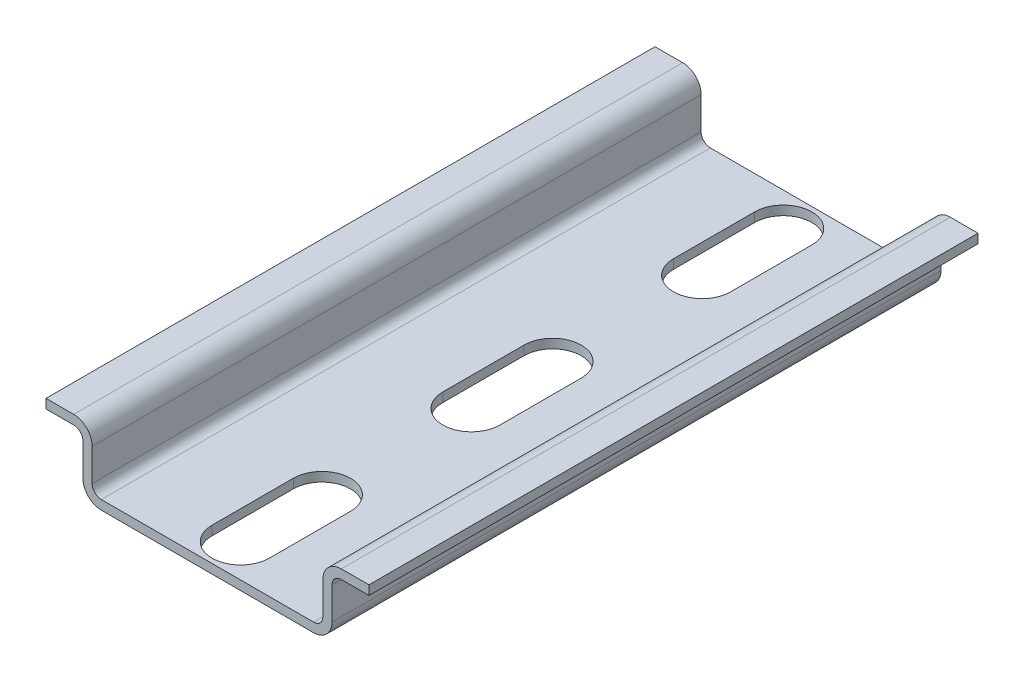
SolidWorks part; units mm, degrees
ref_plane "Спереди" through (0, 0, 0) normal (0, 0, 1) x (1, 0, 0)
ref_plane "Сверху" through (0, 0, 0) normal (0, 1, 0) x (1, 0, 0)
ref_plane "Справа" through (0, 0, 0) normal (1, 0, 0) x (0, 0, -1)
sketch "Эскиз1" plane through (0, 0, 0) normal (0, 0, 1) x (1, 0, 0)
  line L0 (0, 6.5) -> (0, -29.2061) construction
  line L1 (-17.5, 6.5) -> (-14.5, 6.5)
  line L2 (-13.5, 5.5) -> (-13.5, 2)
  line L3 (-11.5, 1) -> (11.5, 1)
  line L4 (-11.5, 0) -> (11.5, 0)
  line L5 (-12.5, 5.5) -> (-12.5, 2)
  line L6 (-17.5, 7.5) -> (-14.5, 7.5)
  line L7 (-17.5, 7.5) -> (-17.5, 6.5)
  line L8 (12.5, 5.5) -> (12.5, 2)
  line L9 (13.5, 5.5) -> (13.5, 2)
  line L10 (17.5, 6.5) -> (14.5, 6.5)
  line L11 (17.5, 7.5) -> (17.5, 6.5)
  line L12 (17.5, 7.5) -> (14.5, 7.5)
  arc A0 (-14.5, 6.5) -> (-13.5, 5.5) centre (-14.5, 5.5) cw
  arc A1 (13.5, 2) -> (11.5, 0) centre (11.5, 2) cw
  arc A2 (-14.5, 7.5) -> (-12.5, 5.5) centre (-14.5, 5.5) cw
  arc A3 (-13.5, 2) -> (-11.5, 0) centre (-11.5, 2) ccw
  arc A4 (14.5, 7.5) -> (12.5, 5.5) centre (14.5, 5.5) ccw
  arc A5 (14.5, 6.5) -> (13.5, 5.5) centre (14.5, 5.5) ccw
  arc A6 (-11.5, 1) -> (-12.5, 2) centre (-11.5, 2) cw
  arc A7 (12.5, 2) -> (11.5, 1) centre (11.5, 2) cw
  point P9 (-13.5, 6.5)
  point P11 (13.5, 0)
  point P12 (-13.5, 0)
  point P18 (0, 0)
  point P19 (0, 1)
  point P34 (-13.5, 0)
  dimension "D1" = 13.5
  dimension "D2" = 6.5
  dimension "D3" = 17.5
  dimension "D5" = 1
extrude "Вытянуть1" add sketch "Эскиз1" along normal blind 220
sketch "Эскиз2" plane through (0, 1, 0) normal (0, 1, 0) x (-1, 0, 0)
  line L0 (0, -5.0137) -> (0, 104.2733) construction
  line L1 (-11.5, 0) -> (11.5, 0) construction
  line L3 (3.1, 21.9) -> (3.1, 13.1)
  line L5 (-3.1, 21.9) -> (-3.1, 13.1)
  arc A0 (3.1, 13.1) -> (-3.1, 13.1) centre (0, 13.1) cw
  arc A1 (-3.1, 21.9) -> (3.1, 21.9) centre (0, 21.9) cw
  dimension "D2" = 10
  dimension "D3" = 15
  dimension "D1" = 6.2
extrude "Вырез-Вытянуть1" cut sketch "Эскиз2" against normal blind 1
pattern_linear "Линейный массив3" count 8 spacing 25 along (0, 0, 1) of "Вырез-Вытянуть1"
sketch "Эскиз3" plane through (0, 0, 0) normal (0, 0, -1) x (-1, 0, 0)
  line L12 (17.5, 6.5) -> (17.5, 7.5)
  line L13 (17.5, 7.5) -> (14.5, 7.5)
  line L14 (12.5, 5.5) -> (12.5, 2)
  line L15 (11.5, 1) -> (-11.5, 1)
  line L16 (-12.5, 2) -> (-12.5, 5.5)
  line L17 (-14.5, 7.5) -> (-17.5, 7.5)
  line L18 (-17.5, 7.5) -> (-17.5, 6.5)
  line L19 (-17.5, 6.5) -> (-14.5, 6.5)
  line L20 (-13.5, 5.5) -> (-13.5, 2)
  line L21 (-11.5, 0) -> (11.5, 0)
  line L22 (13.5, 2) -> (13.5, 5.5)
  line L23 (14.5, 6.5) -> (17.5, 6.5)
  line L24 (17.5, 6.5) -> (17.5, 7.5)
  line L25 (17.5, 7.5) -> (14.5, 7.5)
  line L26 (12.5, 5.5) -> (12.5, 2)
  line L27 (11.5, 1) -> (-11.5, 1)
  line L28 (-12.5, 2) -> (-12.5, 5.5)
  line L29 (-14.5, 7.5) -> (-17.5, 7.5)
  line L30 (-17.5, 7.5) -> (-17.5, 6.5)
  line L31 (-17.5, 6.5) -> (-14.5, 6.5)
  line L32 (-13.5, 5.5) -> (-13.5, 2)
  line L33 (-11.5, 0) -> (11.5, 0)
  line L34 (13.5, 2) -> (13.5, 5.5)
  line L35 (14.5, 6.5) -> (17.5, 6.5)
  arc A8 (14.5, 7.5) -> (12.5, 5.5) centre (14.5, 5.5) ccw
  arc A9 (11.5, 1) -> (12.5, 2) centre (11.5, 2) ccw
  arc A10 (-12.5, 2) -> (-11.5, 1) centre (-11.5, 2) ccw
  arc A11 (-12.5, 5.5) -> (-14.5, 7.5) centre (-14.5, 5.5) ccw
  arc A12 (-13.5, 5.5) -> (-14.5, 6.5) centre (-14.5, 5.5) ccw
  arc A13 (-13.5, 2) -> (-11.5, 0) centre (-11.5, 2) ccw
  arc A14 (11.5, 0) -> (13.5, 2) centre (11.5, 2) ccw
  arc A15 (14.5, 6.5) -> (13.5, 5.5) centre (14.5, 5.5) ccw
  arc A16 (14.5, 7.5) -> (12.5, 5.5) centre (14.5, 5.5) ccw
  arc A17 (11.5, 1) -> (12.5, 2) centre (11.5, 2) ccw
  arc A18 (-12.5, 2) -> (-11.5, 1) centre (-11.5, 2) ccw
  arc A19 (-12.5, 5.5) -> (-14.5, 7.5) centre (-14.5, 5.5) ccw
  arc A20 (-13.5, 5.5) -> (-14.5, 6.5) centre (-14.5, 5.5) ccw
  arc A21 (-13.5, 2) -> (-11.5, 0) centre (-11.5, 2) ccw
  arc A22 (11.5, 0) -> (13.5, 2) centre (11.5, 2) ccw
  arc A23 (14.5, 6.5) -> (13.5, 5.5) centre (14.5, 5.5) ccw
  dimension "D1" = 0
extrude "Вырез-Вытянуть5" cut sketch "Эскиз3" against normal blind 9.5
sketch "Эскиз5" plane through (0, 0, 220) normal (0, 0, 1) x (1, 0, 0)
  line L12 (-17.5, 7.5) -> (-17.5, 6.5)
  line L13 (-17.5, 6.5) -> (-14.5, 6.5)
  line L14 (-13.5, 5.5) -> (-13.5, 2)
  line L15 (-11.5, 0) -> (11.5, 0)
  line L16 (13.5, 2) -> (13.5, 5.5)
  line L17 (14.5, 6.5) -> (17.5, 6.5)
  line L18 (17.5, 6.5) -> (17.5, 7.5)
  line L19 (17.5, 7.5) -> (14.5, 7.5)
  line L20 (12.5, 5.5) -> (12.5, 2)
  line L21 (11.5, 1) -> (-11.5, 1)
  line L22 (-12.5, 2) -> (-12.5, 5.5)
  line L23 (-14.5, 7.5) -> (-17.5, 7.5)
  line L24 (-17.5, 7.5) -> (-17.5, 6.5)
  line L25 (-17.5, 6.5) -> (-14.5, 6.5)
  line L26 (-13.5, 5.5) -> (-13.5, 2)
  line L27 (-11.5, 0) -> (11.5, 0)
  line L28 (13.5, 2) -> (13.5, 5.5)
  line L29 (14.5, 6.5) -> (17.5, 6.5)
  line L30 (17.5, 6.5) -> (17.5, 7.5)
  line L31 (17.5, 7.5) -> (14.5, 7.5)
  line L32 (12.5, 5.5) -> (12.5, 2)
  line L33 (11.5, 1) -> (-11.5, 1)
  line L34 (-12.5, 2) -> (-12.5, 5.5)
  line L35 (-14.5, 7.5) -> (-17.5, 7.5)
  arc A8 (-13.5, 5.5) -> (-14.5, 6.5) centre (-14.5, 5.5) ccw
  arc A9 (-13.5, 2) -> (-11.5, 0) centre (-11.5, 2) ccw
  arc A10 (11.5, 0) -> (13.5, 2) centre (11.5, 2) ccw
  arc A11 (14.5, 6.5) -> (13.5, 5.5) centre (14.5, 5.5) ccw
  arc A12 (14.5, 7.5) -> (12.5, 5.5) centre (14.5, 5.5) ccw
  arc A13 (11.5, 1) -> (12.5, 2) centre (11.5, 2) ccw
  arc A14 (-12.5, 2) -> (-11.5, 1) centre (-11.5, 2) ccw
  arc A15 (-12.5, 5.5) -> (-14.5, 7.5) centre (-14.5, 5.5) ccw
  arc A16 (-13.5, 5.5) -> (-14.5, 6.5) centre (-14.5, 5.5) ccw
  arc A17 (-13.5, 2) -> (-11.5, 0) centre (-11.5, 2) ccw
  arc A18 (11.5, 0) -> (13.5, 2) centre (11.5, 2) ccw
  arc A19 (14.5, 6.5) -> (13.5, 5.5) centre (14.5, 5.5) ccw
  arc A20 (14.5, 7.5) -> (12.5, 5.5) centre (14.5, 5.5) ccw
  arc A21 (11.5, 1) -> (12.5, 2) centre (11.5, 2) ccw
  arc A22 (-12.5, 2) -> (-11.5, 1) centre (-11.5, 2) ccw
  arc A23 (-12.5, 5.5) -> (-14.5, 7.5) centre (-14.5, 5.5) ccw
  dimension "D1" = 0
extrude "Вырез-Вытянуть6" cut sketch "Эскиз5" against normal offset from surface (19.5 mm away) 191 up to face at (0, 4.4, 9.5)
sketch "Эскиз6" plane through (0, 0, 0) normal (0, -1, 0) x (1, 0, 0)
  line L1 (-32.1573, -15.5) -> (40.269, -15.5)
  line L2 (-32.1573, -15.5) -> (-32.1573, 134.5)
  line L3 (-32.1573, 134.5) -> (40.269, 134.5)
  line L4 (40.269, -15.5) -> (40.269, 134.5)
  arc A2 (-3.1, 138.1) -> (3.1, 138.1) centre (0, 138.1) ccw construction
  dimension "D1" = 150
  dimension "D2" = 3.6
extrude "Вырез-Вытянуть7" cut sketch "Эскиз6" against normal blind 10
